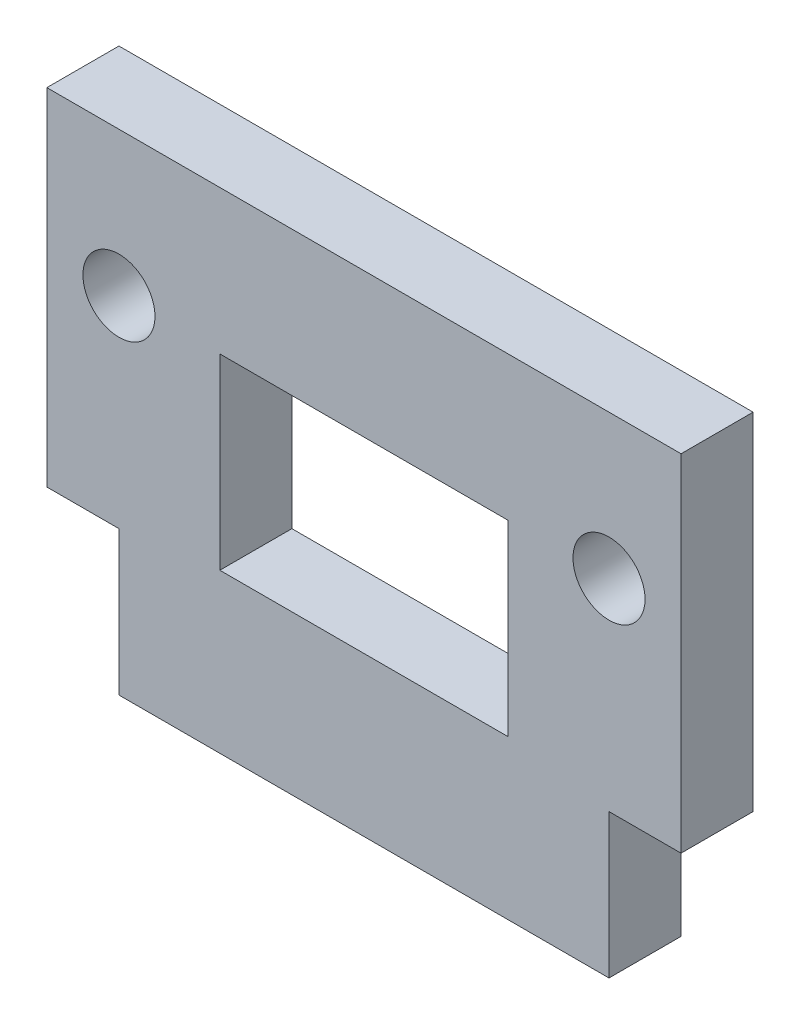
SolidWorks part; units mm, degrees
material "ABS"
ref_plane "Front Plane" through (0, 0, 0) normal (0, 0, 1) x (1, 0, 0)
ref_plane "Top Plane" through (0, 0, 0) normal (0, 1, 0) x (1, 0, 0)
ref_plane "Right Plane" through (0, 0, 0) normal (1, 0, 0) x (0, 0, -1)
sketch "Sketch1" plane through (0, 0, 0) normal (0, 0, 1) x (1, 0, 0)
  line L0 (-11, -12) -> (-8.5, -12)
  line L1 (-8.5, -12) -> (-8.5, -17)
  line L4 (-3, -28) -> (-0.5, -28)
  line L7 (-5, -11.5) -> (-5, -5)
  line L8 (-5, -5) -> (5, -5)
  line L9 (5, -5) -> (5, -11.5)
  line L10 (5, -11.5) -> (-5, -11.5)
  line L12 (-0.5, -28) -> (2, -28)
  line L15 (8.5, -17) -> (8.5, -12)
  line L16 (8.5, -12) -> (11, -12)
  line L17 (11, -12) -> (11, 0)
  line L18 (11, 0) -> (-11, 0)
  line L19 (-11, 0) -> (-11, -12)
  line L20 (-8.5, -17) -> (8.5, -17)
  line L21 (0, -5) -> (0, -11.5) construction
  circle A0 centre (-8.5, -5) radius 1.25
  circle A1 centre (8.5, -5) radius 1.25
  point P20 (0, 0)
  point P22 (0, -5)
  dimension "D10" = 2.5
  dimension "D1" = 12
  dimension "D2" = 22
  dimension "D3" = 12
  dimension "D4" = 5
  dimension "D5" = 10
  dimension "D6" = 6.5
  dimension "D7" = 5
  dimension "D8" = 5
  dimension "D9" = 17
  dimension "D11" = 2.5
  dimension "D12" = 5
  dimension "D13" = 8.5
extrude "Boss-Extrude1" add sketch "Sketch1" along normal blind 2.5 contours L1 L20 L15 L16 L17 L18 L19 L0 L9 L10 L7 L8 A0 A1
sketch "Sketch2" plane through (0, 0, 0) normal (0, 0, -1) x (-1, 0, 0)
  line L0 (8.5, -17) -> (-8.5, -17) construction
  line L1 (6, -4) -> (-6, -4)
  line L2 (6, -4) -> (6, -14)
  line L3 (6, -14) -> (-6, -14)
  line L4 (-6, -4) -> (-6, -14)
  line L5 (6, -4) -> (-6, -14) construction
  line L6 (6, -14) -> (-6, -4) construction
  point P0 (0, -9)
  dimension "D1" = 12
  dimension "D2" = 10
  dimension "D3" = 3
extrude "Cut-Extrude1" [suppressed] cut sketch "Sketch2" against normal blind 1
